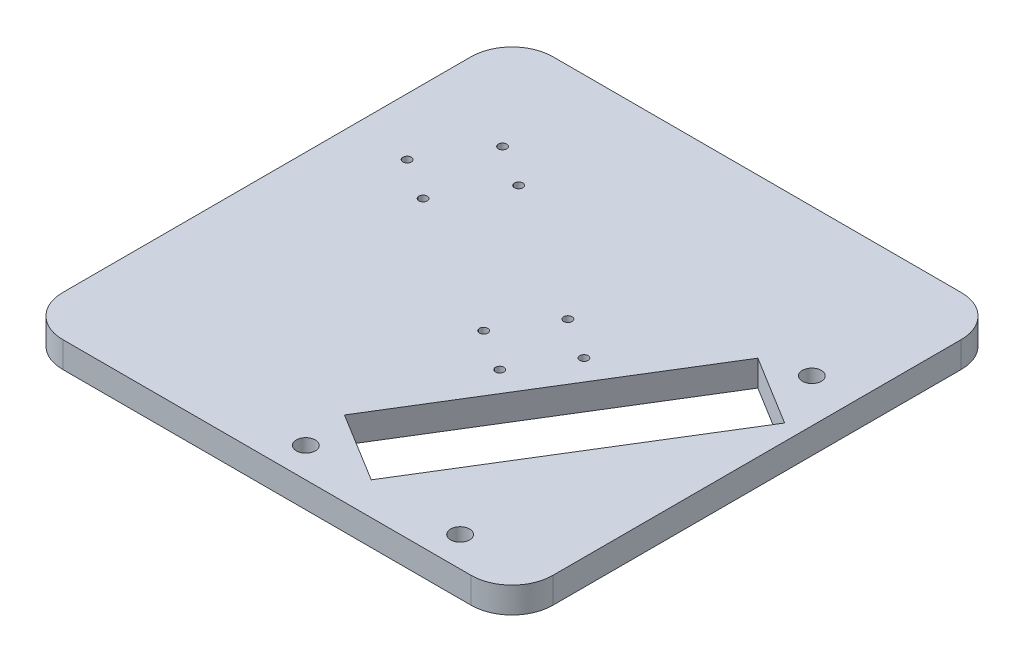
SolidWorks part; units mm, degrees
material "Beech"
ref_plane "Front Plane" through (0, 0, 0) normal (0, 0, 1) x (1, 0, 0)
ref_plane "Top Plane" through (0, 0, 0) normal (0, 1, 0) x (1, 0, 0)
ref_plane "Right Plane" through (0, 0, 0) normal (1, 0, 0) x (0, 0, -1)
sketch "Sketch1" plane through (0, 0, 0) normal (0, 1, 0) x (1, 0, 0)
  line L1 (10, 0) -> (110, 0)
  line L2 (0, 10) -> (0, 110)
  line L3 (10, 120) -> (110, 120)
  line L4 (120, 10) -> (120, 110)
  arc A0 (110, 0) -> (120, 10) centre (110, 10) ccw
  arc A1 (10, 0) -> (0, 10) centre (10, 10) cw
  arc A2 (0, 110) -> (10, 120) centre (10, 110) cw
  arc A3 (110, 120) -> (120, 110) centre (110, 110) cw
  point P7 (120, 0)
  point P10 (0, 0)
  point P13 (0, 120)
  point P16 (120, 120)
  dimension "D3" = 10
  dimension "D1" = 120
  dimension "D2" = 120
extrude "Boss-Extrude1" add sketch "Sketch1" along normal blind 6.35
sketch "Sketch2" plane through (0, 6.35, 0) normal (0, 1, 0) x (1, 0, 0)
  line L0 (58.0317, 5) -> (102.0317, 5) construction
  line L1 (102.0317, 5) -> (113, 94.33) construction
  line L2 (113, 94.33) -> (58.0317, 5) construction
  line L5 (60.4717, 18.5061) -> (77.5052, 8.0247)
  line L6 (77.5052, 8.0247) -> (116.0663, 70.6909)
  line L7 (116.0663, 70.6909) -> (99.0328, 81.1723)
  line L8 (60.4717, 18.5061) -> (99.0328, 81.1723)
  line L9 (10, 0) -> (110, 0) construction
  line L10 (120, 10) -> (120, 110) construction
  circle A0 centre (62.1922, 7.325) radius 2.325
  circle A1 centre (99.9747, 7.325) radius 2.325
  circle A2 centre (109.3931, 84.0319) radius 2.325
  dimension "D6" = 4.65
  dimension "D7" = 4.65
  dimension "D8" = 4.65
  dimension "D1" = 97
  dimension "D2" = 44
  dimension "D3" = 89.33
  dimension "D4" = 5
  dimension "D5" = 7
  dimension "D9" = 20
  dimension "D10" = 73.58
  dimension "D11" = 5
  dimension "D12" = 7.865
  dimension "D13" = 8.6209
extrude "Cut-Extrude1" cut sketch "Sketch2" against normal through all
sketch "Sketch5" plane through (0, 6.35, 0) normal (0, 1, 0) x (1, 0, 0)
  line L0 (79.7522, 49.8392) -> (0, 98.9139) construction
  line L1 (99.0328, 81.1723) -> (60.4717, 18.5061) construction
  line L2 (0, 110) -> (0, 10) construction
  circle A0 centre (69.86, 47.1201) radius 1.025
  circle A1 centre (59.6399, 53.409) radius 1.025
  circle A2 centre (77.721, 59.8952) radius 1.025
  circle A3 centre (67.5009, 66.1841) radius 1.025
  circle A4 centre (13.977, 80.333) radius 1.025
  circle A5 centre (24.1971, 74.0441) radius 1.025
  circle A6 centre (33.1063, 88.5226) radius 1.025
  circle A7 centre (22.8862, 94.8115) radius 1.025
  dimension "D2" = 2.05
  dimension "D3" = 2.05
  dimension "D4" = 2.05
  dimension "D5" = 2.05
  dimension "D14" = 2.05
  dimension "D15" = 2.05
  dimension "D16" = 2.05
  dimension "D17" = 2.05
  dimension "D1" = 90
  dimension "D6" = 7.5
  dimension "D7" = 7.5
  dimension "D8" = 7.5
  dimension "D9" = 7.5
  dimension "D10" = 7
  dimension "D11" = 7
  dimension "D12" = 12
  dimension "D13" = 12
  dimension "D18" = 8.5
  dimension "D19" = 8.5
  dimension "D20" = 8.5
  dimension "D21" = 8.5
  dimension "D22" = 60
  dimension "D23" = 60
  dimension "D24" = 12
  dimension "D25" = 12
extrude "Cut-Extrude2" cut sketch "Sketch5" against normal through all
sketch "Sketch4" plane through (0, 0, 0) normal (0, -1, 0) x (1, 0, 0)
  line L0 (79.7522, -49.8392) -> (96.7857, -39.3578) construction
  line L1 (99.0328, -81.1723) -> (60.4717, -18.5061) construction
  line L2 (77.5052, -8.0247) -> (116.0663, -70.6909) construction
